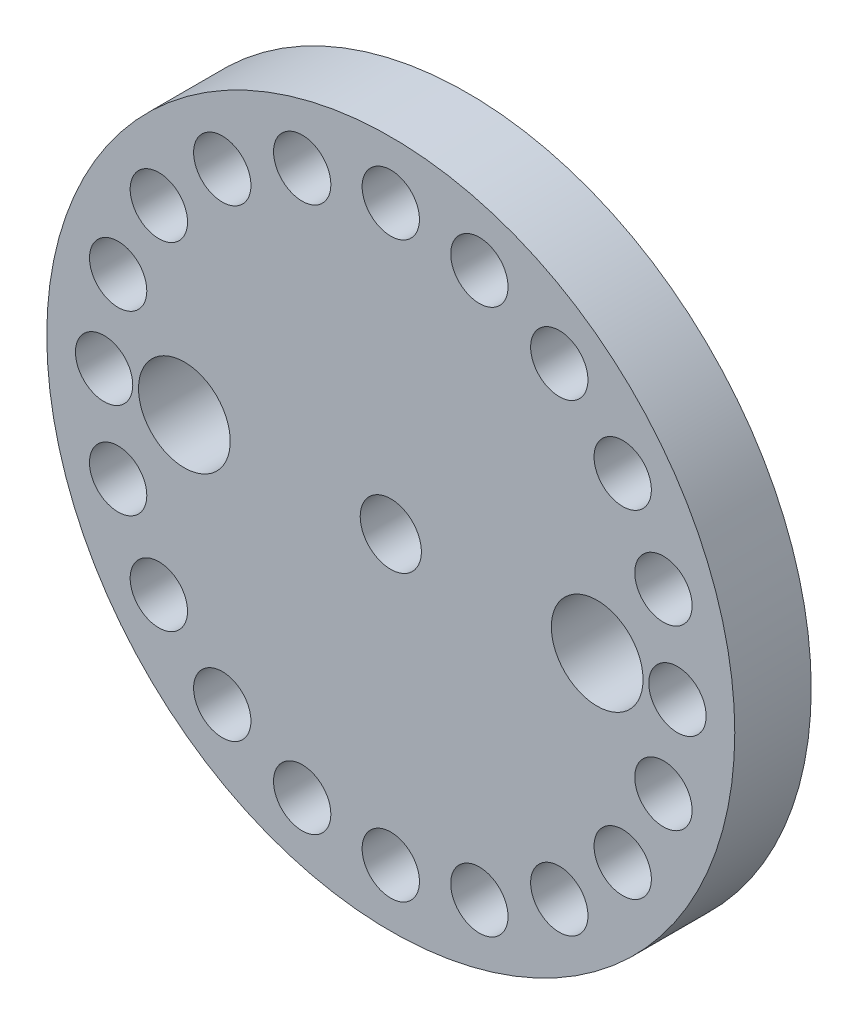
SolidWorks part; units mm, degrees
ref_plane "Front Plane" through (0, 0, 0) normal (0, 0, 1) x (1, 0, 0)
ref_plane "Top Plane" through (0, 0, 0) normal (0, 1, 0) x (1, 0, 0)
ref_plane "Right Plane" through (0, 0, 0) normal (1, 0, 0) x (0, 0, -1)
sketch "Sketch1" plane through (0, 0, 0) normal (0, 0, 1) x (1, 0, 0)
  circle A0 centre (0, 0) radius 45
  circle A1 centre (0, 0) radius 37.5 construction
  circle A2 centre (0, 37.5) radius 3.75
  circle A3 centre (11.5881, 35.6646) radius 3.75
  circle A4 centre (22.0419, 30.3381) radius 3.75
  circle A5 centre (30.3381, 22.0419) radius 3.75
  circle A6 centre (35.6646, 11.5881) radius 3.75
  circle A7 centre (37.5, 0) radius 3.75
  circle A8 centre (35.6646, -11.5881) radius 3.75
  circle A9 centre (30.3381, -22.0419) radius 3.75
  circle A10 centre (22.0419, -30.3381) radius 3.75
  circle A11 centre (11.5881, -35.6646) radius 3.75
  circle A12 centre (0, -37.5) radius 3.75
  circle A13 centre (-11.5881, -35.6646) radius 3.75
  circle A14 centre (-22.0419, -30.3381) radius 3.75
  circle A15 centre (-30.3381, -22.0419) radius 3.75
  circle A16 centre (-35.6646, -11.5881) radius 3.75
  circle A17 centre (-37.5, 0) radius 3.75
  circle A18 centre (-35.6646, 11.5881) radius 3.75
  circle A19 centre (-30.3381, 22.0419) radius 3.75
  circle A20 centre (-22.0419, 30.3381) radius 3.75
  circle A21 centre (-11.5881, 35.6646) radius 3.75
  dimension "D1" = 90
  dimension "D2" = 75
  dimension "D3" = 7.5
  dimension "D4" = 20
extrude "Boss-Extrude1" add sketch "Sketch1" along normal blind 10
sketch "Sketch2" plane through (0, 0, 0) normal (0, 0, -1) x (-1, 0, 0)
  line L0 (0, 33.1061) -> (0, 15.4176) construction
  circle A0 centre (0, 0) radius 27 construction
  circle A1 centre (27, 0) radius 6
  circle A2 centre (-27, 0) radius 6
  dimension "D1" = 54
  dimension "D2" = 12
extrude "Cut-Extrude1" cut sketch "Sketch2" against normal blind 10
sketch "Sketch3" plane through (0, 0, 0) normal (0, 0, -1) x (-1, 0, 0)
  circle A0 centre (0, 0) radius 4
  dimension "D1" = 8
extrude "Cut-Extrude2" cut sketch "Sketch3" against normal blind 13
